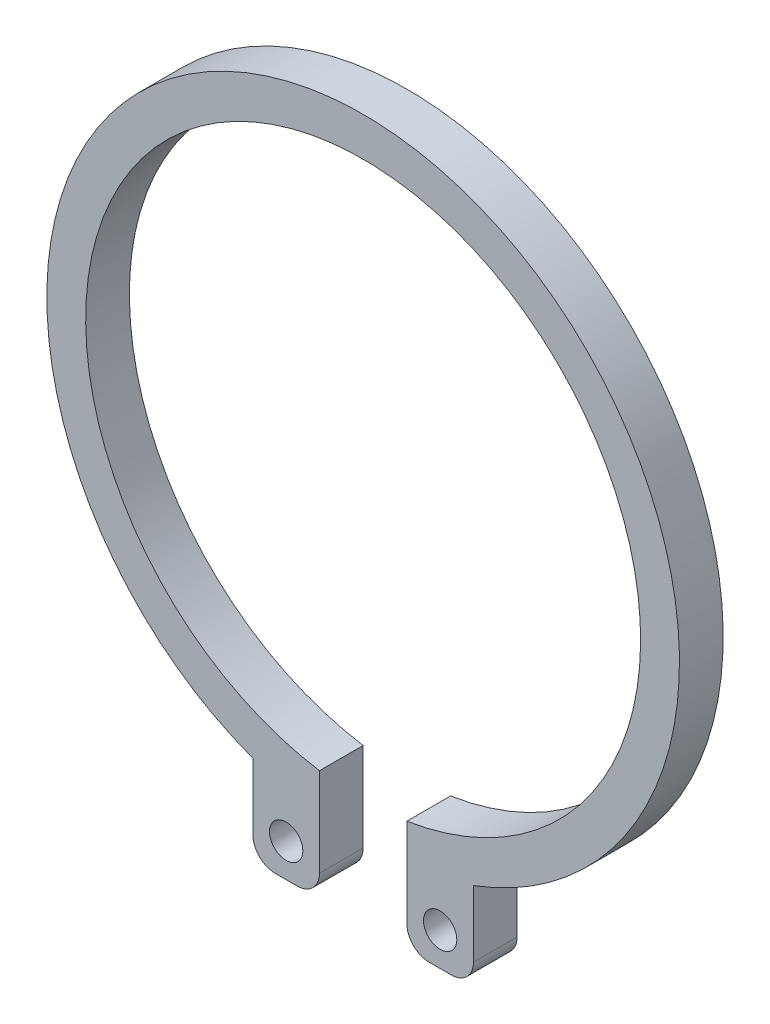
SolidWorks part; units mm, degrees
ref_plane "Front Plane" through (0, 0, 0) normal (0, 0, 1) x (1, 0, 0)
ref_plane "Top Plane" through (0, 0, 0) normal (0, 1, 0) x (1, 0, 0)
ref_plane "Right Plane" through (0, 0, 0) normal (1, 0, 0) x (0, 0, -1)
sketch "Sketch1" plane through (0, 0, 0) normal (0, 0, 1) x (1, 0, 0)
  circle A0 centre (0, 0) radius 3.175
  circle A1 centre (0, 0) radius 3.6195
  dimension "D1" = 6.35
  dimension "D2" = 7.239
extrude "Boss-Extrude1" add sketch "Sketch1" along normal blind 0.5
sketch "Sketch2" plane through (0, 0, 0.5) normal (0, 0, 1) x (1, 0, 0)
  line L0 (0.5, -2.2082) -> (0.5, -4.1388)
  line L2 (-0.5, -2.2082) -> (-0.5, 2.2082)
  line L3 (-0.5, 2.2082) -> (0.5, 2.2082)
  line L4 (0.5, -2.2082) -> (0.5, 2.2082)
  line L5 (-0.5, -2.2082) -> (0.5, 2.2082) construction
  line L6 (-0.5, 2.2082) -> (0.5, -2.2082) construction
  line L7 (0.5, -4.1388) -> (-0.5, -4.1388)
  line L8 (-0.5, -4.1388) -> (-0.5, -2.2082)
  point P0 (0, 0)
  dimension "D1" = 1
extrude "Cut-Extrude1" cut sketch "Sketch2" against normal through all
sketch "Sketch3" plane through (0, 0, 0) normal (0, 0, -1) x (-1, 0, 0)
  line L1 (0.5, -3.1354) -> (1.262, -3.1354)
  line L2 (0.5, -3.1354) -> (0.5, -4.4054)
  line L3 (0.5, -4.4054) -> (1.262, -4.4054)
  line L4 (1.262, -3.1354) -> (1.262, -4.4054)
  line L5 (-0.5, -3.1354) -> (-1.262, -3.1354)
  line L6 (-0.5, -3.1354) -> (-0.5, -4.4054)
  line L7 (-0.5, -4.4054) -> (-1.262, -4.4054)
  line L8 (-1.262, -3.1354) -> (-1.262, -4.4054)
  circle A0 centre (0.881, -4.0244) radius 0.1905
  circle A1 centre (-0.881, -4.0244) radius 0.1905
  dimension "D9" = 0.381
  dimension "D10" = 0.381
  dimension "D1" = 0.762
  dimension "D2" = 1.27
  dimension "D3" = 0.762
  dimension "D4" = 1.27
  dimension "D5" = 0.381
  dimension "D6" = 0.381
  dimension "D7" = 0.381
  dimension "D8" = 0.381
extrude "Boss-Extrude2" add sketch "Sketch3" against normal up to surface (0.5 mm away) up to face at (0, 0.0186, 0.5)
fillet "Fillet1" radius 0.254 4 edges at (-0.5, -4.4054, 0.25) (0.5, -4.4054, 0.25) (-1.262, -4.4054, 0.25) (1.262, -4.4054, 0.25)
